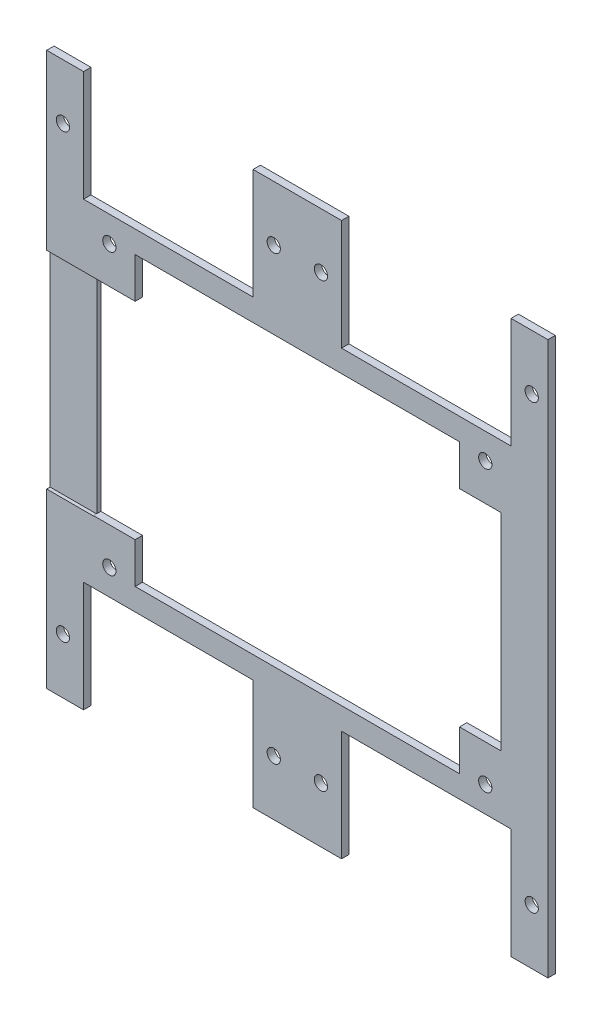
SolidWorks part; units mm, degrees
ref_plane "Front Plane" through (0, 0, 0) normal (0, 0, 1) x (1, 0, 0)
ref_plane "Top Plane" through (0, 0, 0) normal (0, 1, 0) x (1, 0, 0)
ref_plane "Right Plane" through (0, 0, 0) normal (1, 0, 0) x (0, 0, -1)
sketch "Sketch2" plane through (0, 0, 0) normal (0, 0, 1) x (1, 0, 0)
  line L1 (-340, -375) -> (340, -375)
  line L2 (-340, -375) -> (-340, 375)
  line L3 (-340, 375) -> (340, 375)
  line L4 (340, -375) -> (340, 375)
  line L5 (-340, -375) -> (340, 375) construction
  line L6 (-340, 375) -> (340, -375) construction
  point P0 (0, 0)
  dimension "D1" = 750
  dimension "D2" = 680
extrude "Boss-Extrude1" add sketch "Sketch2" along normal blind 10
sketch "Sketch3" plane through (0, 0, 10) normal (0, 0, 1) x (1, 0, 0)
  line L0 (340, 375) -> (-340, 375) construction
  line L1 (-290, 375) -> (-60, 375)
  line L2 (-290, 375) -> (-290, 225)
  line L3 (-290, 225) -> (-60, 225)
  line L4 (-60, 375) -> (-60, 225)
  line L5 (-340, 375) -> (-340, -375) construction
  line L6 (0, 375) -> (0, -375) construction
  line L7 (-340, -375) -> (340, -375) construction
  line L8 (340, 0) -> (-340, 0) construction
  line L9 (340, -375) -> (340, 375) construction
  line L10 (290, 225) -> (60, 225)
  line L11 (60, 375) -> (60, 225)
  line L12 (290, 375) -> (60, 375)
  line L13 (290, 375) -> (290, 225)
  line L14 (290, -375) -> (290, -225)
  line L15 (290, -375) -> (60, -375)
  line L16 (60, -375) -> (60, -225)
  line L17 (290, -225) -> (60, -225)
  line L18 (-290, -225) -> (-60, -225)
  line L19 (-60, -375) -> (-60, -225)
  line L20 (-290, -375) -> (-60, -375)
  line L21 (-290, -375) -> (-290, -225)
  dimension "D1" = 230
  dimension "D2" = 50
  dimension "D3" = 150
extrude "Cut-Extrude1" cut sketch "Sketch3" against normal through all contours L2 L1 L4 L3 | L10 L11 L12 L13 | L18 L19 L20 L21 | L14 L17 L16 L15
sketch "Sketch4" plane through (0, 0, 10) normal (0, 0, 1) x (1, 0, 0)
  line L0 (-318, 300) -> (-290, 300) construction
  line L1 (-290, 375) -> (-290, 225) construction
  line L2 (-318, 300) -> (-315, 375) construction
  line L3 (-290, 375) -> (-340, 375) construction
  line L4 (60, 375) -> (-60, 375) construction
  line L5 (-340, 375) -> (-340, -375) construction
  line L6 (-290, 225) -> (-60, 225) construction
  line L7 (0, 375) -> (0, -375) construction
  line L8 (-60, -375) -> (60, -375) construction
  line L9 (340, 0) -> (-340, 0) construction
  line L10 (340, -375) -> (340, 375) construction
  circle A0 centre (-318, 300) radius 9
  circle A1 centre (-32, 300) radius 9
  circle A2 centre (-255, 190) radius 9
  circle A3 centre (318, 300) radius 9
  circle A4 centre (255, 190) radius 9
  circle A5 centre (32, 300) radius 9
  circle A6 centre (318, -300) radius 9
  circle A7 centre (255, -190) radius 9
  circle A8 centre (32, -300) radius 9
  circle A9 centre (-255, -190) radius 9
  circle A10 centre (-32, -300) radius 9
  circle A11 centre (-318, -300) radius 9
  point P44 (0, 0)
  dimension "D3" = 18
  dimension "D4" = 18
  dimension "D9" = 18
  dimension "D1" = 75
  dimension "D2" = 28
  dimension "D5" = 75
  dimension "D6" = 286
  dimension "D7" = 85
  dimension "D8" = 35
extrude "Cut-Extrude4" cut sketch "Sketch4" against normal through all
sketch "Sketch6" plane through (0, 0, 10) normal (0, 0, 1) x (1, 0, 0)
  line L1 (-220, -195) -> (220, -195)
  line L2 (-220, -195) -> (-220, 195)
  line L3 (-220, 195) -> (220, 195)
  line L4 (220, -195) -> (220, 195)
  line L5 (-220, -195) -> (220, 195) construction
  line L6 (-220, 195) -> (220, -195) construction
  line L7 (-276.5, -140) -> (276.5, -140)
  line L8 (-276.5, -140) -> (-276.5, 140)
  line L9 (-276.5, 140) -> (276.5, 140)
  line L10 (276.5, -140) -> (276.5, 140)
  line L11 (-276.5, -140) -> (276.5, 140) construction
  line L12 (-276.5, 140) -> (276.5, -140) construction
  point P0 (0, 0)
  point P6 (0, 0)
  dimension "D1" = 390
  dimension "D2" = 440
  dimension "D3" = 280
  dimension "D4" = 553
extrude "Cut-Extrude6" cut sketch "Sketch6" against normal through all contours L9 L2 L7 L4 | L2 L9 L4 L3 | L7 L2 L1 L4 | L7 L10 L9 L4 | L9 L8 L7 L2
sketch "Sketch7" plane through (0, 0, 10) normal (0, 0, 1) x (1, 0, 0)
  line L0 (-340, 375) -> (-340, -375) construction
  line L3 (-276.5, 140) -> (-340, 140)
  line L4 (-276.5, 140) -> (-276.5, -140.4975)
  line L5 (-276.5, -140.4975) -> (-340, -140.4975)
  line L6 (-340, 140) -> (-340, -140.4975)
extrude "Cut-Extrude7" cut sketch "Sketch7" against normal blind 4.6 contours L4 L3 L6 L5
